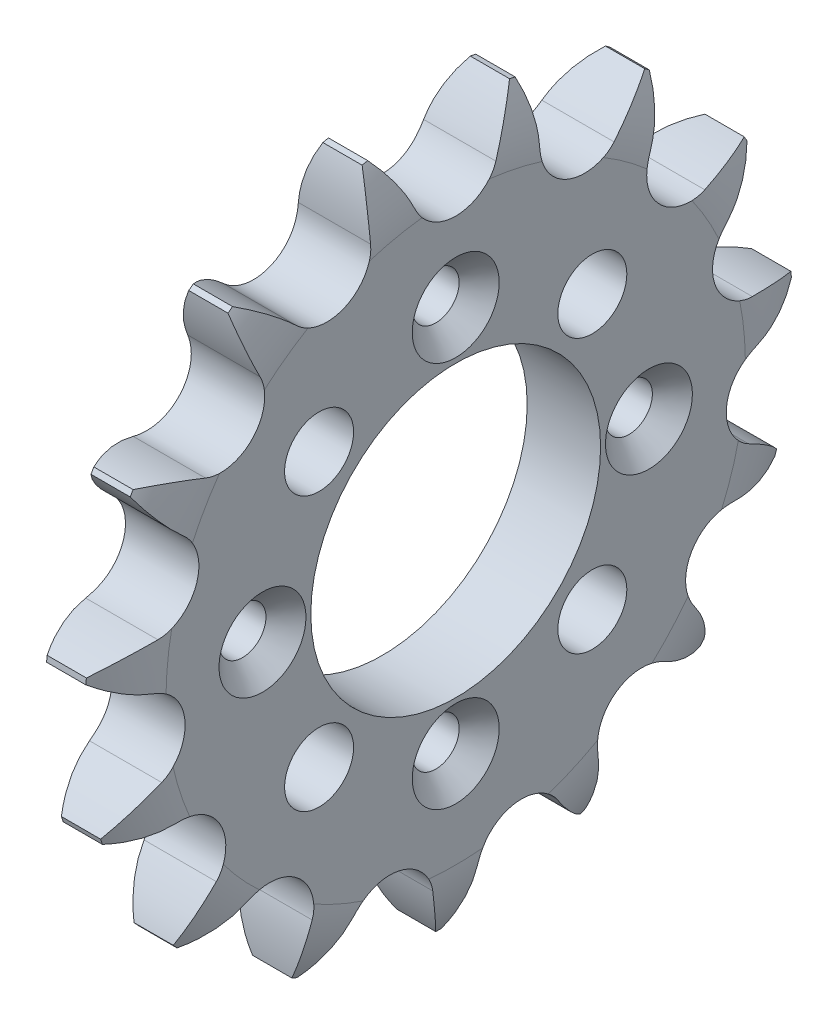
SolidWorks part; units mm, degrees
material "1.0503 (C45)"
ref_plane "Plane1" through (0, 0, 0) normal (0, 0, 1) x (1, 0, 0)
ref_plane "Plane2" through (0, 0, 0) normal (0, 1, 0) x (1, 0, 0)
ref_plane "Plane3" through (0, 0, 0) normal (1, 0, 0) x (0, 0, -1)
sketch "Clipboard" plane through (0, 0, 0) normal (0, 1, 0) x (1, 0, 0)
  line L0 (0, 0) -> (9.2004, -2.4653)
  line L1 (-15, 0) -> (100, 0) construction
  line L2 (0, 0) -> (-0.8203, 0.9272)
  line L3 (0, 0) -> (-8.8973, 3.4006)
  line L4 (0, 0) -> (2.9944, 0.8023)
  line L5 (0, 0) -> (-46.8476, -17.4728)
  line L6 (0, 0) -> (-4.4098, -2.9753)
  line L7 (-0.8203, 0.9272) -> (47.2432, 14.7092)
  line L8 (-76.2, 38.1) -> (-74.4, 38.1)
  line L9 (-73.3242, 40.7328) -> (-72.926, 40.7699)
  line L10 (-73.4529, 9.1872) -> (-63.2129, 9.1872)
  circle A0 centre (0, 0) radius 3.175
  circle A1 centre (0, 0) radius 17.7306
  circle A2 centre (0, 0) radius 37.5
  dimension "Dr" = 6.35
  dimension "MHD" = 35.4612
  dimension "Hub_dia" = 75
  dimension "Num_teeth" = 15
  dimension "Pitch" = 9.525
  dimension "Width" = 3.1
  dimension "Side_relief" = 1.238
  dimension "Side_radius" = 9.525
  dimension "Overall_len" = 50
  dimension "Show_teeth" = 15
  dimension "Thickness" = 5.3196
  dimension "OAL" = 50.0005
  dimension "T_dim" = 1.8
  dimension "Fillet_rad" = 0.4
  dimension "Face_width" = 5.32
  dimension "Num_strands" = 1
  dimension "Transv_pitch" = 10.24
  dimension "Plate_wid" = 8.26
sketch "BasProSke" plane through (0, 0, 0) normal (0, 1, 0) x (1, 0, 0)
  line L0 (-10, 0) -> (60, 0) construction
  line L1 (0, 0) -> (0, 20.9886)
  line L2 (0, 0) -> (5.3196, 0)
  line L3 (5.3196, 0) -> (5.3196, 20.9886)
  line L4 (4.0816, 25.6845) -> (1.238, 25.6845)
  arc A0 (0, 20.9886) -> (1.238, 25.6845) centre (9.525, 20.9886) cw
  arc A1 (5.3196, 20.9886) -> (4.0816, 25.6845) centre (-4.2054, 20.9886) ccw
  dimension "Thickness" = 5.3196
  dimension "D1" = 9.525
  dimension "G1" = 1.238
  dimension "G2" = 1.238
  dimension "Diameter" = 51.369
revolve "Base-Revolve" add sketch "BasProSke" angle 360 about L0
sketch "TooCutSke" plane through (0, 0, 0) normal (1, 0, 0) x (0, 0, -1)
  line L0 (0, 22.9381) -> (2.9518, 21.6851) construction
  line L1 (0, 0) -> (0, 107) construction
  line L2 (0, 22.9381) -> (-10, 22.9381) construction
  line L3 (0, 22.9381) -> (-2.9518, 21.6851) construction
  arc A0 (2.9518, 21.6851) -> (5.5304, 25.5938) centre (14.876, 16.6236) cw
  arc A1 (2.9518, 21.6851) -> (-2.9518, 21.6851) centre (0, 22.9381) cw
  arc A2 (-2.9518, 21.6851) -> (-5.5304, 25.5938) centre (-14.876, 16.6236) ccw
  arc A3 (5.5304, 25.5938) -> (-5.5304, 25.5938) centre (0, 0) ccw
  dimension "R1" = 3.2067
  dimension "R2" = 12.954
  dimension "Overcut" = 26.1845
  dimension "Seat_radius" = 22.9381
  dimension "X" = 134
extrude "ToothCut" cut sketch "TooCutSke" along normal through all
pattern_circular "TeethCuts" count 15 every 24 about axis through (-10, 0, 0) along (1, 0, 0) of "ToothCut"
sketch "HubNeaOneSke" plane through (0, 0, 0) normal (-1, 0, 0) x (0, 0, 1)
  circle A0 centre (0, 0) radius 17.7306
  dimension "Diameter" = 35.4612
extrude "HubNearOne" [suppressed] add sketch "HubNeaOneSke" along normal blind 44.6809
fillet "HubNearOneFillet" [suppressed] radius 0.4
sketch "HubNeaBotSke" plane through (0, 0, 0) normal (-1, 0, 0) x (0, 0, 1)
  circle A0 centre (0, 0) radius 17.7306
  dimension "Diameter" = 35.4612
extrude "HubNearBoth" [suppressed] add sketch "HubNeaBotSke" along normal blind 22.3405
fillet "HubNearBothFillet" [suppressed] radius 0.4
ref_plane "FarPln" through (5.3196, 0, 0) normal (1, 0, 0) x (0, 0, -1)
sketch "HubFarSke" plane through (5.3196, 0, 0) normal (1, 0, 0) x (0, 0, -1)
  circle A0 centre (0, 0) radius 17.7306
  dimension "Diameter" = 35.4612
extrude "HubFar" [suppressed] add sketch "HubFarSke" along normal blind 22.3405
fillet "HubFarFillet" [suppressed] radius 0.4
sketch "BorSke" plane through (0, 0, 0) normal (1, 0, 0) x (0, 0, -1)
  circle A0 centre (0, 0) radius 5
  dimension "Diameter" = 10
extrude "Bore" cut sketch "BorSke" along normal mid plane 100.001
sketch "KeySke" plane through (0, 0, 0) normal (1, 0, 0) x (0, 0, -1)
  line L0 (-2, 0) -> (-2, 6.8)
  line L1 (-2, 6.8) -> (2, 6.8)
  line L2 (2, 6.8) -> (2, 0)
  line L3 (0, 0) -> (0, 34) construction
  line L4 (-2, 0) -> (2, 0)
  dimension "Offset" = 6.8
  dimension "Width" = 4
extrude "Keyway" [suppressed] cut sketch "KeySke" along normal mid plane 100.001
pattern_circular "Keyway2" [suppressed] count 2 every 90 about axis through (-10, 0, 0) along (1, 0, 0)
sketch "Sketch1" plane through (5.3196, 0, 0) normal (1, 0, 0) x (0, 0, -1)
  circle A0 centre (0, 0) radius 10.5
  dimension "D1" = 21
extrude "Cut-Extrude1" cut sketch "Sketch1" against normal blind 10
hole_wizard "CSK for M3 Countersunk Flat Head Screw2" positions "Sketch4" profile "Sketch3" countersink size "M3" standard "ISO" end condition through all
sketch "Sketch4" plane through (5.3196, 0, 0) normal (1, 0, 0) x (0, 0, -1)
  circle A0 centre (0, 0) radius 14
  point P0 (0, 14)
  point P2 (-14, 0)
  point P4 (14, 0)
  point P6 (0, -14)
  dimension "D1" = 28
sketch "Sketch3" plane through (5.3196, 14, 0) normal (0, 1, 0) x (0, 0, -1)
  line L0 (0, 0) -> (0, 5.3196)
  line L1 (0, 5.3196) -> (1.7, 5.3196)
  line L2 (1.7, 5.3196) -> (1.7, 1.45)
  line L3 (1.7, 1.45) -> (3.15, 0)
  line L5 (3.15, 0) -> (0, 0)
  line L6 (-1.7, 1.45) -> (-3.15, 0) construction
  line L11 (0, -6.35) -> (0, 107.95) construction
  dimension "Thru Hole Dia." = 3.4
  dimension "Thru Hole Depth" = 5.3196
  dimension "Near C'Sink Dia." = 6.3
  dimension "Near C'Sink Angle" = 90
sketch "Sketch5" plane through (5.3196, 0, 0) normal (1, 0, 0) x (0, 0, -1)
  line L0 (-8.0094, 0) -> (0, 0) construction
  line L1 (0, 0) -> (0, 9.8995) construction
  line L2 (0, 9.8995) -> (-9.8995, 9.8995) construction
  line L3 (-9.8995, 9.8995) -> (0, 0) construction
  circle A0 centre (-9.8995, 9.8995) radius 2.5
  circle A1 centre (9.8995, 9.8995) radius 2.5
  circle A2 centre (9.8995, -9.8995) radius 2.5
  circle A3 centre (-9.8995, -9.8995) radius 2.5
  dimension "D1" = 5
  dimension "D2" = 14
extrude "Cut-Extrude2" cut sketch "Sketch5" against normal blind 10
equation "' \"Pitch@Clipboard\" = 12.7"
equation "' \"Num_strands@Clipboard\" = 1"
equation "' \"Num_teeth@Clipboard\" = 9"
equation "' \"Hub_dia@Clipboard\" = 50"
equation "' \"Overall_len@Clipboard\" = 3"
equation "' \"Diameter@BorSke\" = 12"
equation "' \"T_dim@Clipboard\" = 1"
equation "' \"Width@KeySke\" = 2"
equation "' \"Dr@Clipboard\" = 8.51"
equation "' \"Face_width@Clipboard\" = 7.2"
equation "' \"Side_radius@Clipboard\" = 12.7"
equation "' \"Side_relief@Clipboard\" = 1.27"
equation "' \"Transv_pitch@Clipboard\" = 13.92"
equation "' \"Show_teeth@Clipboard\" = 9"
equation "' \"Fillet_rad@Clipboard\" = 0.6"
equation "' \"Plate_wid@Clipboard\" = 11.8"
equation "\"Num_teeth@Clipboard\" = int( \"Num_teeth@Clipboard\" )"
equation "\"Num_teeth@Clipboard\" = ((sgn( \"Num_teeth@Clipboard\" - 5.0)+1)*( \"Num_teeth@Clipboard\" - 5.0))/2 +5.0"
equation "\"Num_teeth@Clipboard\" = ((sgn( \"Num_teeth@Clipboard\" - 200.0)-1)*( \"Num_teeth@Clipboard\" - 200.0))/-2 +200.0"
equation "\"MHD@Clipboard\" = \"Pitch@Clipboard\" * (1.0 / tan(3.14159265 / \"Num_teeth@Clipboard\" )) - 1.04 * \"Plate_wid@Clipboard\" - 0.76"
equation "\"Thickness@Clipboard\"  = \"Face_width@Clipboard\" + (\"Num_strands@Clipboard\" - 1) * \"Transv_pitch@Clipboard\""
equation "\"OAL@Clipboard\" = \"Thickness@Clipboard\" + 2 * \"Fillet_rad@Clipboard\" + 1"
equation "\"MHD@Clipboard\" = ((sgn( \"MHD@Clipboard\" - \"Hub_dia@Clipboard\" )-1)*( \"MHD@Clipboard\" - \"Hub_dia@Clipboard\" ))/-2+ \"Hub_dia@Clipboard\""
equation "\"OAL@Clipboard\" = ((sgn( \"OAL@Clipboard\" - \"Overall_len@Clipboard\" )+1)*( \"OAL@Clipboard\" - \"Overall_len@Clipboard\" ))/2 + \"Overall_len@Clipboard\" + 0.0005"
equation "\"Num_teeth@TeethCuts\" = int( \"Show_teeth@Clipboard\" ) + 1"
equation "\"Num_teeth@TeethCuts\" = ((sgn( \"Num_teeth@TeethCuts\" - \"Num_teeth@Clipboard\" )-1)*( \"Num_teeth@TeethCuts\" - \"Num_teeth@Clipboard\" ))/-2+ \"Num_teeth@Clipboard\""
equation "\"Num_teeth@TeethCuts\" = ((sgn( \"Num_teeth@TeethCuts\" - 2.0)+1)*( \"Num_teeth@TeethCuts\" - 2.0))/2 +2.0"
equation "\"Angle@TeethCuts\" = 360.0 / \"Num_teeth@Clipboard\""
equation "\"Seat_radius@TooCutSke\" = ( \"Pitch@Clipboard\" / 2.0) / sin(3.14159265 / \"Num_teeth@Clipboard\" ) - \"Dr@Clipboard\" / 2.0 + \"Dr@Clipboard\" * 0.505"
equation "\"R1@TooCutSke\"  = \"Dr@Clipboard\" * 0.505"
equation "\"X@TooCutSke\" = 140.0 - (90.0 / \"Num_teeth@Clipboard\")"
equation "\"R2@TooCutSke\" = 0.12 * \"Dr@Clipboard\" * ( \"Num_teeth@Clipboard\" + 2.0)"
equation "\"Overcut@TooCutSke\" = 0.5 + 0.625 * \"Pitch@Clipboard\" - 0.5 * \"Dr@Clipboard\"  +  \"Pitch@Clipboard\" / 2.0 / sin(3.14159265 / \"Num_teeth@Clipboard\" )"
equation "\"Diameter@BasProSke\" = 2.0 * ( 0.625 * \"Pitch@Clipboard\" - 0.5 * \"Dr@Clipboard\"  +  \"Pitch@Clipboard\" / 2.0 / sin(3.14159265 / \"Num_teeth@Clipboard\" ))"
equation "\"Thickness@BasProSke\"  = \"Thickness@Clipboard\""
equation "\"G1@BasProSke\" =  \"Side_relief@Clipboard\""
equation "\"G2@BasProSke\" =  \"Side_relief@Clipboard\""
equation "\"D1@BasProSke\" =  \"Side_radius@Clipboard\""
equation "\"Diameter@HubNeaOneSke\" = \"MHD@Clipboard\""
equation "\"Length@HubNearOne\" = \"OAL@Clipboard\" - \"Thickness@BasProSke\""
equation "\"Diameter@HubNeaBotSke\" = \"MHD@Clipboard\""
equation "\"Length@HubNearBoth\" = ( \"OAL@Clipboard\" - \"Thickness@BasProSke\" ) / 2.0"
equation "\"D1@HubNearOneFillet\" = \"Fillet_rad@Clipboard\""
equation "\"D1@HubNearBothFillet\" = \"Fillet_rad@Clipboard\""
equation "\"Thickness@FarPln\" = \"Thickness@BasProSke\""
equation "\"Diameter@HubFarSke\" = \"MHD@Clipboard\""
equation "\"Length@HubFar\" = ( \"OAL@Clipboard\" - \"Thickness@BasProSke\" ) / 2.0"
equation "\"D1@HubFarFillet\" = \"Fillet_rad@Clipboard\""
equation "\"D1@Bore\" = \"OAL@Clipboard\" * 2.0"
equation "\"D1@Keyway\" = \"OAL@Clipboard\" * 2.0"
equation "\"Offset@KeySke\" = \"T_dim@Clipboard\" + \"Diameter@BorSke\" / 2.0"
